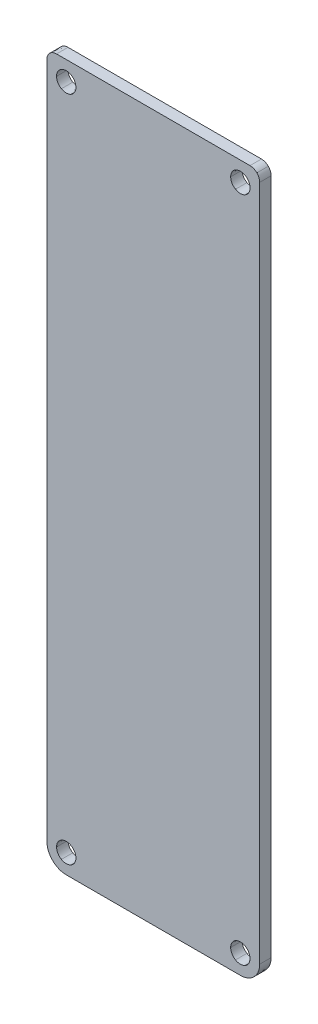
SolidWorks part; units mm, degrees
ref_plane "Plan de face" through (0, 0, 0) normal (0, 0, 1) x (1, 0, 0)
ref_plane "Plan de dessus" through (0, 0, 0) normal (0, 1, 0) x (1, 0, 0)
ref_plane "Plan de droite" through (0, 0, 0) normal (1, 0, 0) x (0, 0, -1)
sketch "Model" plane through (0, 0, 0) normal (0, 0, 1) x (1, 0, 0)
  line L1773 (110.49, -34.8139) -> (110.49, -38.6239)
  line L1774 (83.82, -33.5439) -> (109.22, -33.5439)
  line L1775 (82.55, -38.6239) -> (82.55, -34.8139)
  line L1776 (82.55, -39.8939) -> (82.55, -123.7139)
  line L1777 (110.49, -39.8939) -> (110.49, -123.7139)
  line L1778 (82.55, -39.8939) -> (82.55, -38.6239)
  line L1779 (110.49, -39.8939) -> (110.49, -38.6239)
  line L1780 (85.09, -126.2539) -> (107.95, -126.2539)
  spline S0 degree 3 poles (109.22, -36.0839) (109.22, -36.5377) (108.9779, -36.9569) (108.585, -37.1838) knots 0 0 0 0 1 1 1 1
  spline S1 degree 3 poles (108.585, -37.1838) (108.1921, -37.4106) (107.7079, -37.4106) (107.315, -37.1838) knots 0 0 0 0 1 1 1 1
  spline S2 degree 3 poles (107.315, -37.1838) (106.9221, -36.9569) (106.68, -36.5377) (106.68, -36.0839) knots 0 0 0 0 1 1 1 1
  spline S3 degree 3 poles (106.68, -36.0839) (106.68, -35.6302) (106.9221, -35.2109) (107.315, -34.9841) knots 0 0 0 0 1 1 1 1
  spline S4 degree 3 poles (107.315, -34.9841) (107.7079, -34.7572) (108.1921, -34.7572) (108.585, -34.9841) knots 0 0 0 0 1 1 1 1
  spline S5 degree 3 poles (108.585, -34.9841) (108.9779, -35.2109) (109.22, -35.6302) (109.22, -36.0839) knots 0 0 0 0 1 1 1 1
  spline S6 degree 3 poles (86.36, -36.0839) (86.36, -36.5377) (86.1179, -36.9569) (85.725, -37.1838) knots 0 0 0 0 1 1 1 1
  spline S7 degree 3 poles (85.725, -37.1838) (85.3321, -37.4106) (84.8479, -37.4106) (84.455, -37.1838) knots 0 0 0 0 1 1 1 1
  spline S8 degree 3 poles (84.455, -37.1838) (84.0621, -36.9569) (83.82, -36.5377) (83.82, -36.0839) knots 0 0 0 0 1 1 1 1
  spline S9 degree 3 poles (83.82, -36.0839) (83.82, -35.6302) (84.0621, -35.2109) (84.455, -34.9841) knots 0 0 0 0 1 1 1 1
  spline S10 degree 3 poles (84.455, -34.9841) (84.8479, -34.7572) (85.3321, -34.7572) (85.725, -34.9841) knots 0 0 0 0 1 1 1 1
  spline S11 degree 3 poles (85.725, -34.9841) (86.1179, -35.2109) (86.36, -35.6302) (86.36, -36.0839) knots 0 0 0 0 1 1 1 1
  spline S12 degree 3 poles (110.49, -34.8139) (110.49, -34.4771) (110.3562, -34.1541) (110.118, -33.9159) knots 0 0 0 0 1 1 1 1
  spline S13 degree 3 poles (110.118, -33.9159) (109.8799, -33.6777) (109.5568, -33.5439) (109.22, -33.5439) knots 0 0 0 0 1 1 1 1
  spline S14 degree 3 poles (83.82, -33.5439) (83.4832, -33.5439) (83.1601, -33.6777) (82.922, -33.9159) knots 0 0 0 0 1 1 1 1
  spline S15 degree 3 poles (82.922, -33.9159) (82.6838, -34.1541) (82.55, -34.4771) (82.55, -34.8139) knots 0 0 0 0 1 1 1 1
  spline S16 degree 3 poles (82.55, -123.7139) (82.55, -124.3876) (82.8176, -125.0336) (83.2939, -125.51) knots 0 0 0 0 1 1 1 1
  spline S17 degree 3 poles (83.2939, -125.51) (83.7703, -125.9863) (84.4163, -126.2539) (85.09, -126.2539) knots 0 0 0 0 1 1 1 1
  spline S18 degree 3 poles (107.95, -126.2539) (108.6236, -126.2539) (109.2697, -125.9863) (109.7461, -125.51) knots 0 0 0 0 1 1 1 1
  spline S19 degree 3 poles (109.7461, -125.51) (110.2224, -125.0336) (110.49, -124.3876) (110.49, -123.7139) knots 0 0 0 0 1 1 1 1
  spline S20 degree 3 poles (86.36, -123.7139) (86.36, -124.1677) (86.1179, -124.5869) (85.725, -124.8138) knots 0 0 0 0 1 1 1 1
  spline S21 degree 3 poles (85.725, -124.8138) (85.3321, -125.0406) (84.8479, -125.0406) (84.455, -124.8138) knots 0 0 0 0 1 1 1 1
  spline S22 degree 3 poles (84.455, -124.8138) (84.0621, -124.5869) (83.82, -124.1677) (83.82, -123.7139) knots 0 0 0 0 1 1 1 1
  spline S23 degree 3 poles (83.82, -123.7139) (83.82, -123.2602) (84.0621, -122.8409) (84.455, -122.6141) knots 0 0 0 0 1 1 1 1
  spline S24 degree 3 poles (84.455, -122.6141) (84.8479, -122.3872) (85.3321, -122.3872) (85.725, -122.6141) knots 0 0 0 0 1 1 1 1
  spline S25 degree 3 poles (85.725, -122.6141) (86.1179, -122.8409) (86.36, -123.2602) (86.36, -123.7139) knots 0 0 0 0 1 1 1 1
  spline S26 degree 3 poles (109.22, -123.7139) (109.22, -124.1677) (108.9779, -124.5869) (108.585, -124.8138) knots 0 0 0 0 1 1 1 1
  spline S27 degree 3 poles (108.585, -124.8138) (108.1921, -125.0406) (107.7079, -125.0406) (107.315, -124.8138) knots 0 0 0 0 1 1 1 1
  spline S28 degree 3 poles (107.315, -124.8138) (106.9221, -124.5869) (106.68, -124.1677) (106.68, -123.7139) knots 0 0 0 0 1 1 1 1
  spline S29 degree 3 poles (106.68, -123.7139) (106.68, -123.2602) (106.9221, -122.8409) (107.315, -122.6141) knots 0 0 0 0 1 1 1 1
  spline S30 degree 3 poles (107.315, -122.6141) (107.7079, -122.3872) (108.1921, -122.3872) (108.585, -122.6141) knots 0 0 0 0 1 1 1 1
  spline S31 degree 3 poles (108.585, -122.6141) (108.9779, -122.8409) (109.22, -123.2602) (109.22, -123.7139) knots 0 0 0 0 1 1 1 1
extrude "Boss.-Extru.1" add sketch "Model" along normal blind 1.5
